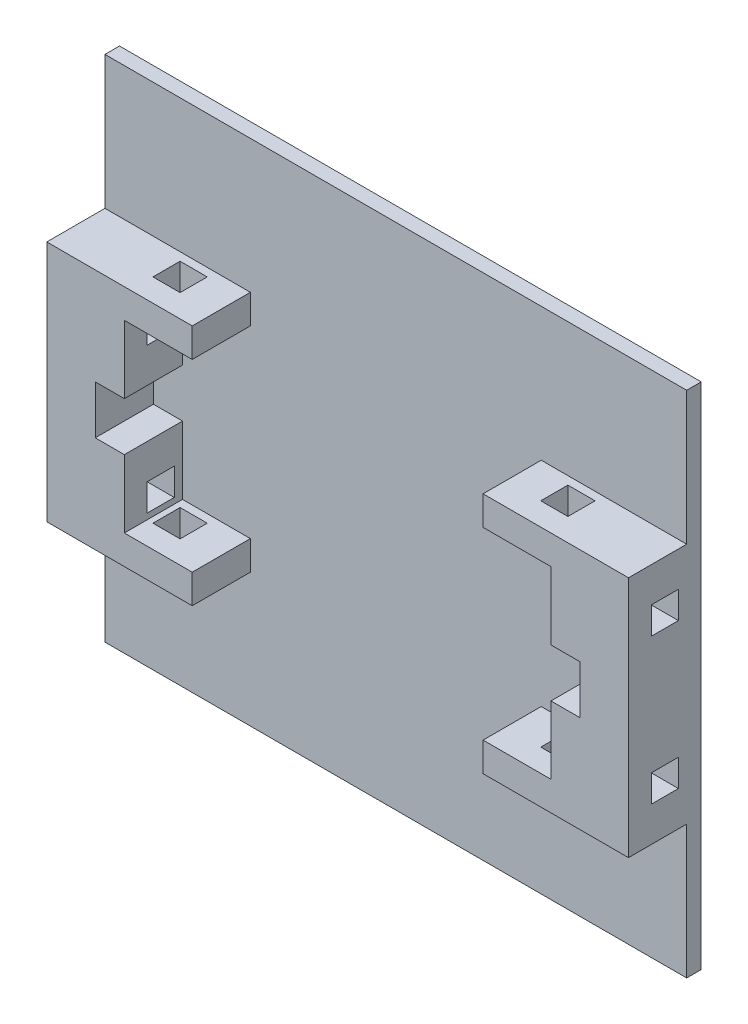
SolidWorks part; units mm, degrees
ref_plane "Plano frontal" through (0, 0, 0) normal (0, 0, 1) x (1, 0, 0)
ref_plane "Plano superior" through (0, 0, 0) normal (0, 1, 0) x (1, 0, 0)
ref_plane "Plano direito" through (0, 0, 0) normal (1, 0, 0) x (0, 0, -1)
sketch "Esboço1" plane through (0, 0, 0) normal (0, 0, 1) x (1, 0, 0)
  line L0 (-5, 0) -> (5, 0) construction
  line L1 (25, 0) -> (-25, 0) construction
  line L2 (0, 0) -> (0, -12.5) construction
  line L3 (25, -12.5) -> (-25, -12.5) construction
  line L4 (-21, 0) -> (-5, 0) construction
  line L5 (-25, -12.5) -> (-25, 12.5)
  line L6 (-25, 12.5) -> (25, 12.5)
  line L7 (0, 12.5) -> (0, 0) construction
  line L8 (20, -12.5) -> (-20, -12.5) construction
  line L12 (-15, -12.5) -> (15, -12.5)
  line L23 (21, 0) -> (5, 0) construction
  line L31 (25, -12.5) -> (25, 12.5)
  line L32 (-25, -12.5) -> (-15, -12.5)
  line L33 (15, -12.5) -> (25, -12.5)
  circle A0 centre (-13, 0) radius 8.3
  circle A1 centre (13, 0) radius 8.3
extrude "Ressalto-extrusão1" add sketch "Esboço1" along normal blind 1.5
sketch "Esboço2" plane through (0, 0, 1.5) normal (0, 0, 1) x (1, 0, 0)
  line L0 (-20, -12.5) -> (-25, -12.5)
  line L1 (0, -12.5) -> (0, 12.5) construction
  line L2 (20, -12.5) -> (-20, -12.5) construction
  line L3 (-25, -12.5) -> (25, -12.5) construction
  line L4 (22, -2.5) -> (22, -9.5)
  line L5 (-25, 12.5) -> (-25, -12.5) construction
  line L6 (-22, -9.5) -> (-15, -9.5)
  line L7 (-15, -9.5) -> (-15, -12.5)
  line L8 (-15, -12.5) -> (-20, -12.5)
  line L9 (-25, -12.5) -> (-25, -2.5)
  line L10 (-25, -2.5) -> (-22, -2.5)
  line L11 (-22, -2.5) -> (-22, -9.5)
  line L12 (25, -2.5) -> (22, -2.5)
  line L13 (25, -12.5) -> (25, -2.5)
  line L14 (15, -12.5) -> (20, -12.5)
  line L15 (25, 12.5) -> (-25, 12.5) construction
  line L16 (15, -9.5) -> (15, -12.5)
  line L17 (-25, 0) -> (25, 0) construction
  line L18 (25, -12.5) -> (25, 12.5) construction
  line L19 (22, -9.5) -> (15, -9.5)
  line L20 (20, -12.5) -> (25, -12.5)
  line L21 (20, 12.5) -> (-20, 12.5) construction
  line L22 (20, 12.5) -> (25, 12.5)
  line L23 (22, 9.5) -> (15, 9.5)
  line L24 (15, 9.5) -> (15, 12.5)
  line L25 (15, 12.5) -> (20, 12.5)
  line L26 (25, 12.5) -> (25, 2.5)
  line L27 (25, 2.5) -> (22, 2.5)
  line L28 (-22, 2.5) -> (-22, 9.5)
  line L29 (-25, 2.5) -> (-22, 2.5)
  line L30 (-25, 12.5) -> (-25, 2.5)
  line L31 (-15, 12.5) -> (-20, 12.5)
  line L32 (-15, 9.5) -> (-15, 12.5)
  line L33 (-22, 9.5) -> (-15, 9.5)
  line L34 (22, 2.5) -> (22, 9.5)
  line L35 (-20, 12.5) -> (-25, 12.5)
extrude "Ressalto-extrusão2" add sketch "Esboço2" along normal blind 6
sketch "Esboço3" plane through (0, -12.5, 0) normal (0, -1, 0) x (1, 0, 0)
  line L0 (-25, 3.75) -> (-15, 3.75) construction
  line L1 (-25, 7.5) -> (-25, 0) construction
  line L2 (-15, 7.5) -> (-15, 1.5) construction
  line L3 (-15, 3.75) -> (-20, 3.75) construction
  line L4 (-20, 3.75) -> (-20, 7.5) construction
  line L5 (-25, 7.5) -> (-15, 7.5) construction
  line L6 (0, 0) -> (0, 8.9122) construction
  line L7 (-21.4, 2.35) -> (-18.6, 2.35)
  line L8 (-21.4, 2.35) -> (-21.4, 5.15)
  line L9 (-21.4, 5.15) -> (-18.6, 5.15)
  line L10 (-18.6, 2.35) -> (-18.6, 5.15)
  line L11 (-21.4, 2.35) -> (-18.6, 5.15) construction
  line L12 (-21.4, 5.15) -> (-18.6, 2.35) construction
  line L13 (-25, 0) -> (25, 0) construction
  line L14 (21.4, 5.15) -> (18.6, 2.35) construction
  line L15 (21.4, 2.35) -> (18.6, 5.15) construction
  line L16 (18.6, 2.35) -> (18.6, 5.15)
  line L17 (21.4, 5.15) -> (18.6, 5.15)
  line L18 (21.4, 2.35) -> (21.4, 5.15)
  line L19 (21.4, 2.35) -> (18.6, 2.35)
extrude "Corte-extrusão1" cut sketch "Esboço3" against normal through all
sketch "Esboço4" plane through (-25, 0, 0) normal (-1, 0, 0) x (0, 0, 1)
  line L2 (3.75, 2.5) -> (3.75, 12.5) construction
  line L5 (3.75, -2.5) -> (3.75, -12.5) construction
  line L9 (0, 12.5) -> (7.5, 12.5) construction
  line L10 (5.15, 8.9) -> (2.35, 8.9)
  line L11 (5.15, 8.9) -> (5.15, 6.1)
  line L12 (5.15, 6.1) -> (2.35, 6.1)
  line L13 (2.35, 8.9) -> (2.35, 6.1)
  line L14 (5.15, 8.9) -> (2.35, 6.1) construction
  line L15 (5.15, 6.1) -> (2.35, 8.9) construction
  line L16 (5.15, -6.1) -> (2.35, -6.1)
  line L17 (5.15, -6.1) -> (5.15, -8.9)
  line L18 (5.15, -8.9) -> (2.35, -8.9)
  line L19 (2.35, -6.1) -> (2.35, -8.9)
  line L20 (5.15, -6.1) -> (2.35, -8.9) construction
  line L21 (5.15, -8.9) -> (2.35, -6.1) construction
  point P12 (3.75, 7.5)
  point P17 (3.75, -7.5)
  point P26 (3.75, 12.5)
extrude "Corte-extrusão2" cut sketch "Esboço4" against normal through all
sketch "Esboço6" plane through (0, 0, 0) normal (0, 0, -1) x (-1, 0, 0)
  line L0 (-25, 12.5) -> (-25, -12.5)
  line L1 (-30, -12.5) -> (-25, -12.5)
  line L2 (-30, -12.5) -> (-30, 12.5)
  line L3 (-30, 12.5) -> (-25, 12.5)
  line L4 (30, -12.5) -> (30, 12.5)
  line L5 (-30, -12.5) -> (30, 12.5) construction
  line L6 (-30, 12.5) -> (30, -12.5) construction
  line L7 (25, 12.5) -> (25, -12.5)
  line L8 (25, 12.5) -> (30, 12.5)
  line L9 (25, -12.5) -> (30, -12.5)
  point P0 (0, 0)
extrude "Ressalto-extrusão5" add sketch "Esboço6" against normal up to surface (7.5 mm away) up to face at (20.6667, -8.1667, 7.5)
sketch "Esboço7" plane through (30, 0, 0) normal (1, 0, 0) x (0, 0, -1)
  line L0 (-2.35, -6.1) -> (-5.15, -6.1) construction
  line L1 (-2.35, -8.9) -> (-2.35, -6.1) construction
  line L2 (-5.15, -8.9) -> (-2.35, -8.9) construction
  line L3 (-5.15, -6.1) -> (-5.15, -8.9) construction
  line L4 (-2.35, -6.1) -> (-5.15, -6.1)
  line L5 (-2.35, -8.9) -> (-2.35, -6.1)
  line L6 (-5.15, -8.9) -> (-2.35, -8.9)
  line L7 (-5.15, -6.1) -> (-5.15, -8.9)
  line L8 (-2.35, 6.1) -> (-2.35, 8.9) construction
  line L9 (-2.35, 8.9) -> (-5.15, 8.9) construction
  line L10 (-5.15, 8.9) -> (-5.15, 6.1) construction
  line L11 (-5.15, 6.1) -> (-2.35, 6.1) construction
  line L12 (-2.35, 6.1) -> (-2.35, 8.9)
  line L13 (-2.35, 8.9) -> (-5.15, 8.9)
  line L14 (-5.15, 8.9) -> (-5.15, 6.1)
  line L15 (-5.15, 6.1) -> (-2.35, 6.1)
extrude "Corte-extrusão3" cut sketch "Esboço7" against normal up to surface (60 mm away) up to face at (-30, 0, 3.75)
sketch "Esboço8" plane through (0, 0, 0) normal (0, 0, -1) x (-1, 0, 0)
  line L1 (30, 26.25) -> (-30, 26.25)
  line L2 (30, 26.25) -> (30, -26.25)
  line L3 (30, -26.25) -> (-30, -26.25)
  line L4 (-30, 26.25) -> (-30, -26.25)
  line L5 (30, 26.25) -> (-30, -26.25) construction
  line L6 (30, -26.25) -> (-30, 26.25) construction
  circle A0 centre (13, 0) radius 8.3
  circle A1 centre (-13, 0) radius 8.3
  point P6 (0, 0)
extrude "Ressalto-extrusão6" add sketch "Esboço8" against normal blind 1.5
sketch "Esboço9" plane through (0, 0, 1.5) normal (0, 0, 1) x (1, 0, 0)
  circle A0 centre (-13, 0) radius 8.3 construction
  circle A1 centre (13, 0) radius 8.3 construction
  circle A2 centre (-13, 0) radius 8.3
  circle A3 centre (13, 0) radius 8.3
extrude "Ressalto-extrusão7" add sketch "Esboço9" against normal through all
